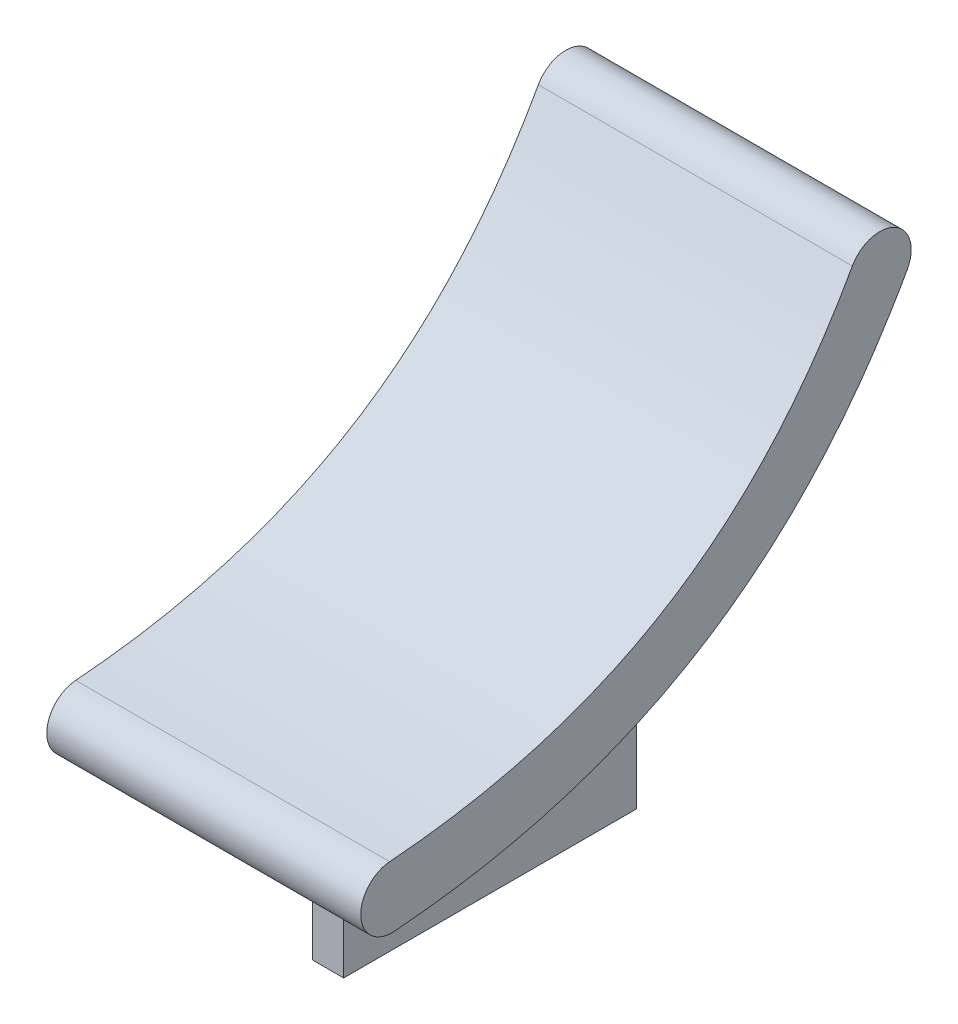
SolidWorks part; units mm, degrees
ref_plane "Front Plane" through (0, 0, 0) normal (0, 0, 1) x (1, 0, 0)
ref_plane "Top Plane" through (0, 0, 0) normal (0, 1, 0) x (1, 0, 0)
ref_plane "Right Plane" through (0, 0, 0) normal (1, 0, 0) x (0, 0, -1)
sketch "Sketch1" plane through (0, 0, 0) normal (1, 0, 0) x (0, 0, -1)
  line L0 (0, 0) -> (14, 0)
  line L1 (14, 0) -> (14, 18)
  line L2 (0, 0) -> (0, 8)
  line L3 (0, 8) -> (14, 18)
  dimension "D1" = 14
  dimension "D2" = 18
  dimension "D3" = 8
extrude "Boss-Extrude1" add sketch "Sketch1" along normal mid plane 1.5
sketch "Sketch2" plane through (0, 0, 0) normal (1, 0, 0) x (0, 0, -1)
  arc A0 (-4.5503, 10.4643) -> (-4.3158, 7.4735) centre (-4.4331, 8.9689) ccw
  arc A1 (17.552, 24.0566) -> (20.1742, 22.5991) centre (18.8631, 23.3279) cw
  spline S0 degree 3 poles (-4.5503, 10.4643) (6.6377, 11.3414) (13.1724, 16.1772) (17.552, 24.0566) knots 0 0 0 0 1 1 1 1
  spline S1 degree 1 poles (-4.3158, 7.4735) (20.1742, 22.5991) knots 0 0 1 1 construction
  spline S2 degree 3 poles (-4.3158, 7.4735) (-3.5832, 7.5309) (-2.1006, 7.6832) (0.6858, 8.1183) (3.9569, 8.9172) (7.5207, 10.2825) (10.7361, 12.0487) (13.5993, 14.1937) (16.1191, 16.6868) (18.3091, 19.4776) (19.5887, 21.5458) (20.1742, 22.5991) knots 0 0 0 0 0.0625 0.125 0.25 0.375 0.5 0.625 0.75 0.875 1 1 1 1
  dimension "D1" = 3
extrude "Boss-Extrude2" add sketch "Sketch2" along normal mid plane 15
